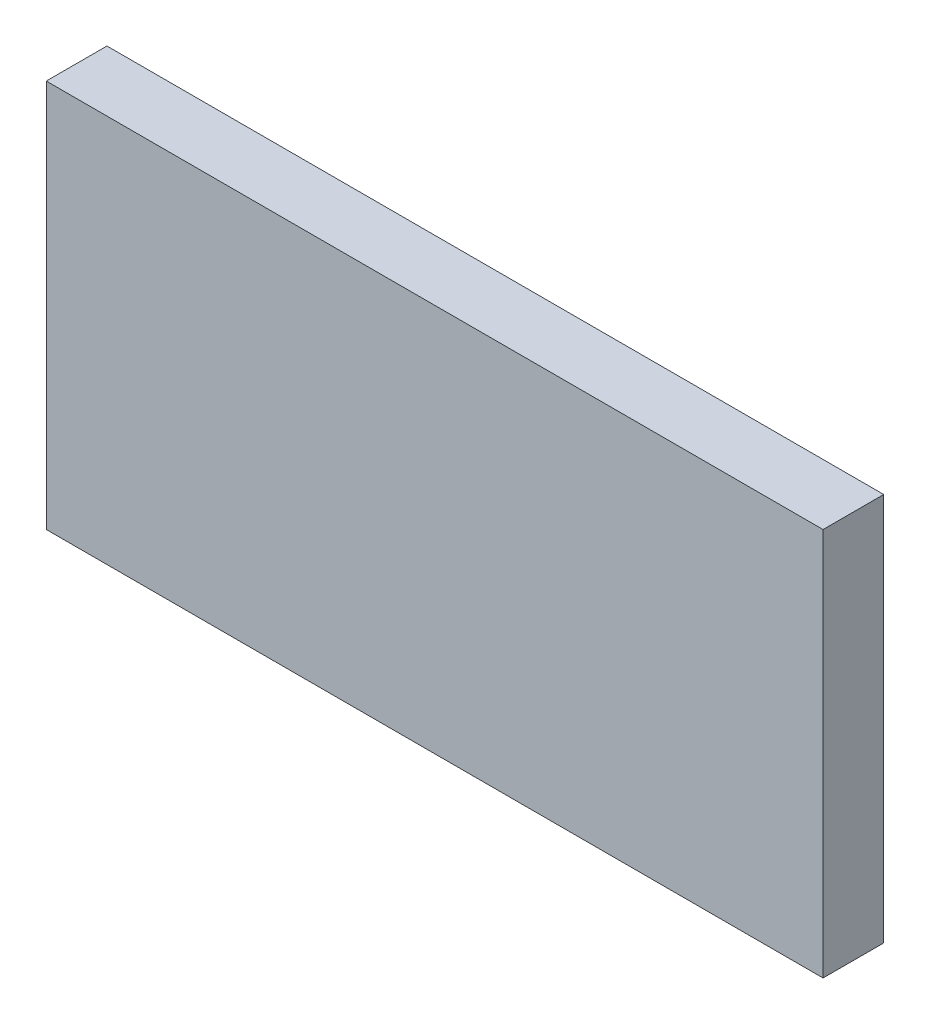
SolidWorks part; units mm, degrees
ref_plane "Front Plane" through (0, 0, 0) normal (0, 0, 1) x (1, 0, 0)
ref_plane "Top Plane" through (0, 0, 0) normal (0, 1, 0) x (1, 0, 0)
ref_plane "Right Plane" through (0, 0, 0) normal (1, 0, 0) x (0, 0, -1)
sketch "Sketch1" plane through (0, 0, 0) normal (0, 0, 1) x (1, 0, 0)
  line L1 (-32, 16) -> (32, 16)
  line L2 (-32, 16) -> (-32, -16)
  line L3 (-32, -16) -> (32, -16)
  line L4 (32, 16) -> (32, -16)
  line L5 (-32, 16) -> (32, -16) construction
  line L6 (-32, -16) -> (32, 16) construction
  point P0 (0, 0)
  dimension "D1" = 32
  dimension "D2" = 64
extrude "Boss-Extrude1" add sketch "Sketch1" along normal blind 5
